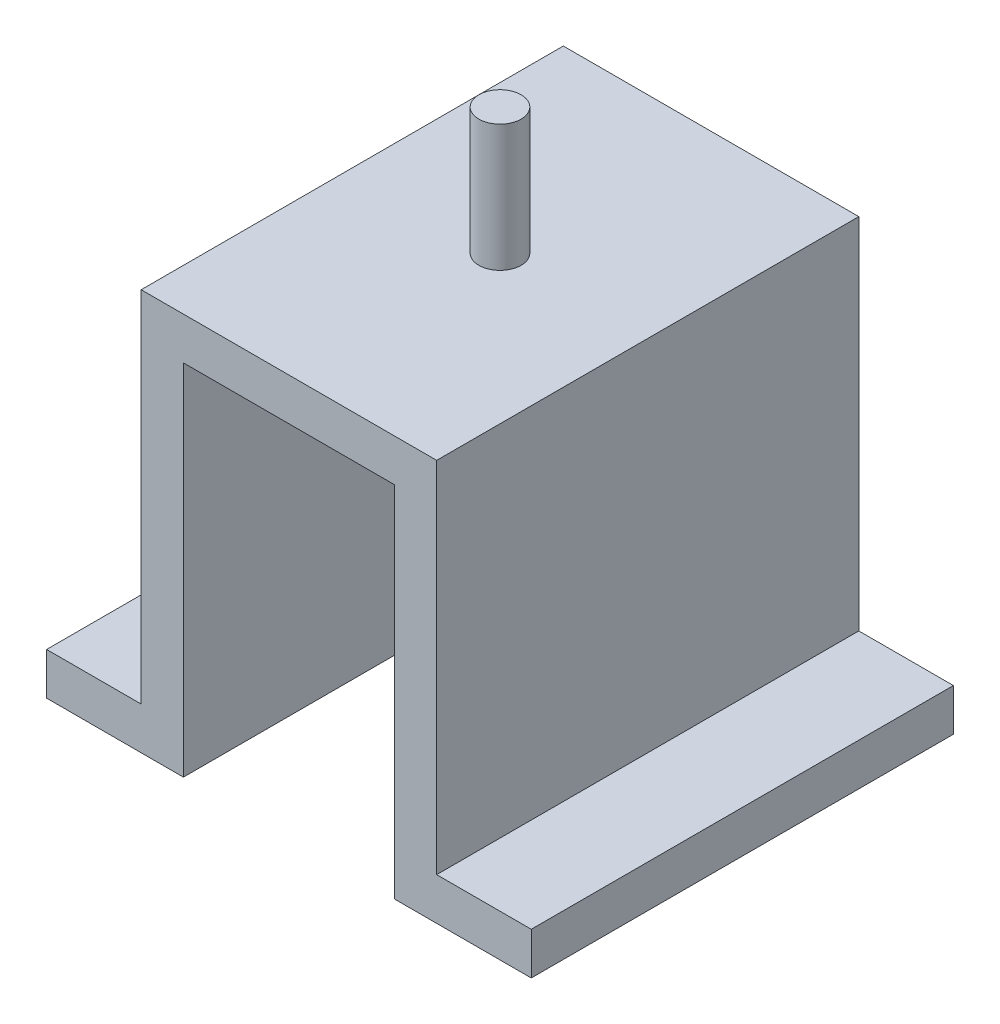
SolidWorks part; units mm, degrees
ref_plane "Front Plane" through (0, 0, 0) normal (0, 0, 1) x (1, 0, 0)
ref_plane "Top Plane" through (0, 0, 0) normal (0, 1, 0) x (1, 0, 0)
ref_plane "Right Plane" through (0, 0, 0) normal (1, 0, 0) x (0, 0, -1)
sketch "Sketch1" plane through (0, 0, 0) normal (0, 0, 1) x (1, 0, 0)
  line L0 (0, 0) -> (0, 22.5728) construction
  line L1 (-57.404, -45.4855) -> (-25, -45.4855)
  line L2 (25, 39.5145) -> (35, 39.5145)
  line L3 (35, 39.5145) -> (35, -35.4855)
  line L4 (35, -35.4855) -> (57.404, -35.4855)
  line L5 (57.404, -35.4855) -> (57.404, -45.4855)
  line L6 (57.404, -45.4855) -> (25, -45.4855)
  line L7 (-57.404, -35.4855) -> (-57.404, -45.4855)
  line L8 (25, 39.5145) -> (25, -45.4855)
  line L9 (-35, -35.4855) -> (-57.404, -35.4855)
  line L10 (-35, 39.5145) -> (-35, -35.4855)
  line L11 (-25, 39.5145) -> (-35, 39.5145)
  line L12 (-25, 39.5145) -> (-25, -45.4855)
  dimension "D1" = 10
  dimension "D2" = 85
  dimension "D3" = 10
  dimension "D4" = 25
extrude "Boss-Extrude1" add sketch "Sketch1" along normal blind 100
sketch "Sketch2" plane through (0, 39.5145, 0) normal (0, 1, 0) x (1, 0, 0)
  line L1 (-35, 0) -> (35, 0)
  line L2 (-35, 0) -> (-35, -100)
  line L3 (-35, -100) -> (35, -100)
  line L4 (35, 0) -> (35, -100)
extrude "Boss-Extrude2" add sketch "Sketch2" along normal blind 10
sketch "Sketch3" plane through (0, 49.5145, 0) normal (0, 1, 0) x (1, 0, 0)
  line L0 (35, 0) -> (-35, 0) construction
  circle A0 centre (0, -50) radius 5
  dimension "D1" = 10
  dimension "D2" = 50
extrude "Boss-Extrude3" add sketch "Sketch3" along normal blind 30
